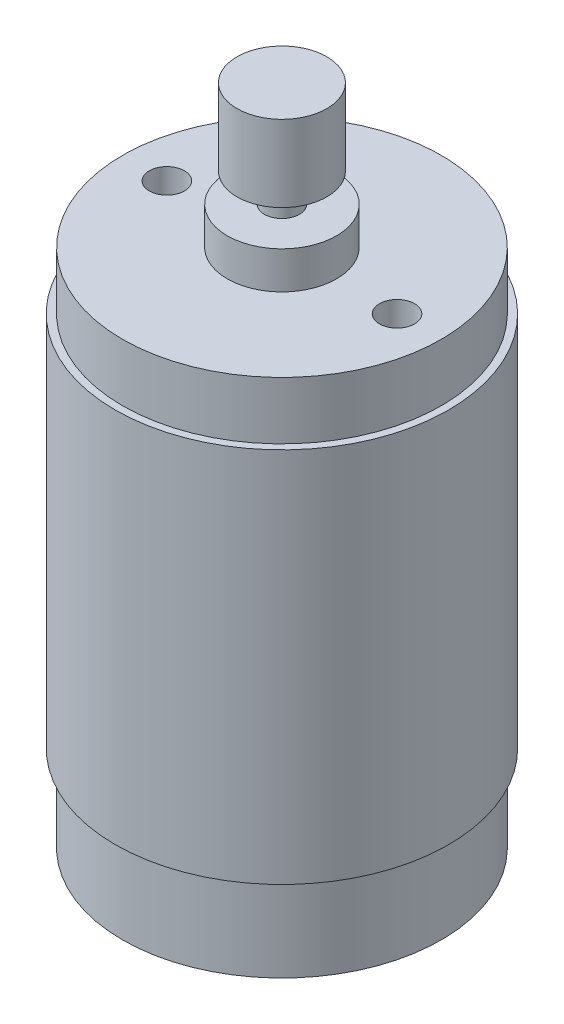
SolidWorks part; units mm, degrees
ref_plane "Front Plane" through (0, 0, 0) normal (0, 0, 1) x (1, 0, 0)
ref_plane "Top Plane" through (0, 0, 0) normal (0, 1, 0) x (1, 0, 0)
ref_plane "Right Plane" through (0, 0, 0) normal (1, 0, 0) x (0, 0, -1)
sketch "Sketch1" plane through (0, 0, 0) normal (1, 0, 0) x (0, 0, -1)
  line L0 (0, 0) -> (0, 36.2612)
  line L1 (0, 0) -> (1.5748, 0)
  line L2 (1.5748, 0) -> (1.5748, 5.4102)
  line L3 (1.5748, 5.4102) -> (4.9911, 5.4102)
  line L4 (4.9911, 5.4102) -> (4.9911, 7.9756)
  line L5 (4.9911, 7.9756) -> (14.4209, 7.9756)
  line L6 (14.4209, 7.9756) -> (14.4209, 15.7734)
  line L7 (14.4209, 15.7734) -> (15.0812, 15.7734)
  line L8 (15.0812, 15.7734) -> (15.0812, 49.8348)
  line L9 (15.0812, 49.8348) -> (14.4209, 49.8348)
  line L10 (14.4209, 49.8348) -> (14.4209, 55.0418)
  line L11 (14.4209, 55.0418) -> (4.9467, 55.0418)
  line L12 (4.9467, 55.0418) -> (4.9467, 58.42)
  line L13 (4.9467, 58.42) -> (1.5875, 58.42)
  line L14 (1.5875, 58.42) -> (1.5875, 61.0235)
  line L15 (1.5875, 61.0235) -> (4.064, 61.0235)
  line L16 (4.064, 61.0235) -> (4.064, 67.945)
  line L17 (4.064, 67.945) -> (0, 67.945)
  line L18 (0, 67.945) -> (0, 36.2612)
  point P9 (4.9911, 6.6929)
  dimension "D1" = 67.945
  dimension "D2" = 15.0812
  dimension "D3" = 14.4208
  dimension "D4" = 34.0614
  dimension "D5" = 1.5748
  dimension "D6" = 4.9911
  dimension "D7" = 5.4102
  dimension "D8" = 2.5654
  dimension "D9" = 7.7978
  dimension "D10" = 5.207
  dimension "D11" = 4.9466
  dimension "D12" = 3.3782
  dimension "D13" = 6.9215
  dimension "D14" = 4.064
  dimension "D15" = 1.5875
revolve "Revolve1" add sketch "Sketch1" angle 360 about L18
sketch "Sketch2" plane through (0, 55.0418, 0) normal (0, 1, 0) x (1, 0, 0)
  line L0 (0, 14.4209) -> (0, -14.4209) construction
  circle A0 centre (0, 0) radius 14.4209 construction
  circle A1 centre (-10.414, 0) radius 1.5875
  circle A2 centre (10.414, 0) radius 1.5875
  point P9 (-10.4775, -0.8911)
  dimension "D2" = 3.175
  dimension "D1" = 20.828
extrude "Cut-Extrude1" cut sketch "Sketch2" against normal blind 6.35
